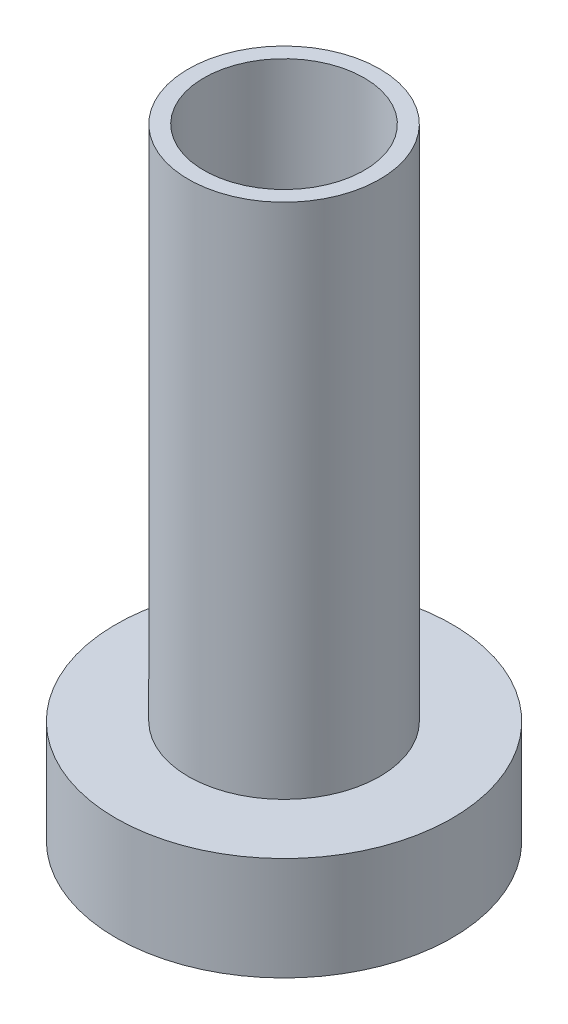
SolidWorks part; units mm, degrees
ref_plane "Front Plane" through (0, 0, 0) normal (0, 0, 1) x (1, 0, 0)
ref_plane "Top Plane" through (0, 0, 0) normal (0, 1, 0) x (1, 0, 0)
ref_plane "Right Plane" through (0, 0, 0) normal (1, 0, 0) x (0, 0, -1)
sketch "Sketch1" plane through (0, 0, 0) normal (0, 1, 0) x (1, 0, 0)
  circle A0 centre (0, 0) radius 3.25
extrude "Boss-Extrude1" add sketch "Sketch1" along normal blind 2
sketch "Sketch6" plane through (0, 0, 0) normal (0, -1, 0) x (-1, 0, 0)
  circle A0 centre (0, 0) radius 1.85
extrude "Boss-Extrude3" add sketch "Sketch6" against normal blind 12
sketch "Sketch7" plane through (0, 0, 0) normal (0, -1, 0) x (-1, 0, 0)
  circle A0 centre (0, 0) radius 1.55
extrude "Cut-Extrude1" cut sketch "Sketch7" against normal through all
